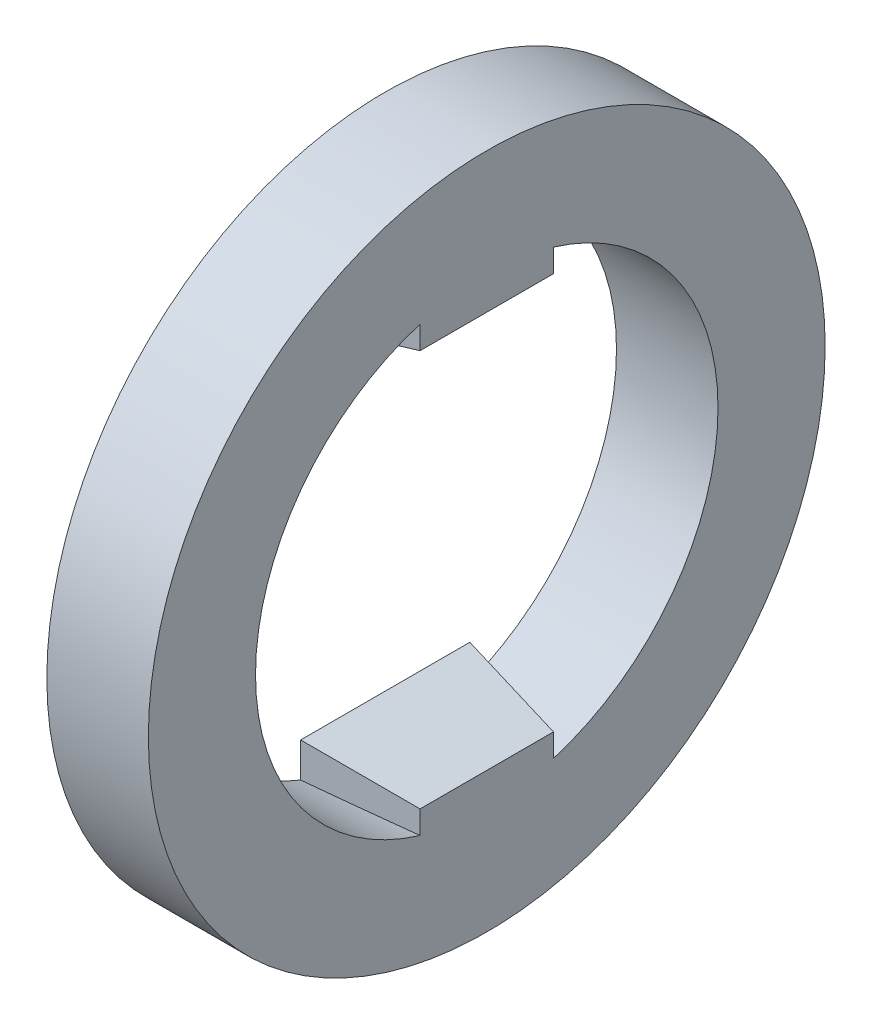
SolidWorks part; units mm, degrees
material "ABS"
ref_plane "Front Plane" through (0, 0, 0) normal (1, 0, 0) x (0, 1, 0)
ref_plane "Top Plane" through (0, 0, 0) normal (0, 0, 1) x (0, 1, 0)
ref_plane "Right Plane" through (0, 0, 0) normal (0, 1, 0) x (-1, 0, 0)
sketch "Sketch1" plane through (0, 0, 0) normal (1, 0, 0) x (0, 1, 0)
  circle A0 centre (0, 0) radius 4.1
  circle A1 centre (0, 0) radius 6
  dimension "D1" = 8.2
  dimension "D2" = 12
extrude "Boss-Extrude1" add sketch "Sketch1" along normal mid plane 1.8
sketch "Sketch2" plane through (0, 0, 0) normal (1, 0, 0) x (0, 1, 0)
  line L0 (5.8095, 1.5) -> (3.2, 1.5)
  line L1 (3.2, 1.5) -> (3.2, -1.5)
  line L2 (3.2, -1.5) -> (5.8095, -1.5)
  line L3 (0, 4.1) -> (0, 0) construction
  line L4 (0, 0) -> (3.2, 0) construction
  line L5 (-5.8095, 1.5) -> (-3.2, 1.5)
  line L6 (-3.2, -1.5) -> (-5.8095, -1.5)
  line L7 (-3.2, 1.5) -> (-3.2, -1.5)
  circle A0 centre (0, 0) radius 4.1 construction
  circle A3 centre (0, 0) radius 6 construction
  arc A4 (-5.8095, 1.5) -> (-5.8095, -1.5) centre (0, 0) ccw
  arc A5 (5.8095, -1.5) -> (5.8095, 1.5) centre (0, 0) ccw
  dimension "D1" = 3
  dimension "D2" = 3.2
extrude "Boss-Extrude2" add sketch "Sketch2" along normal blind 1.8 draft 10 from surface at -0.9 starting at face at (-0.9, 0, -6)
